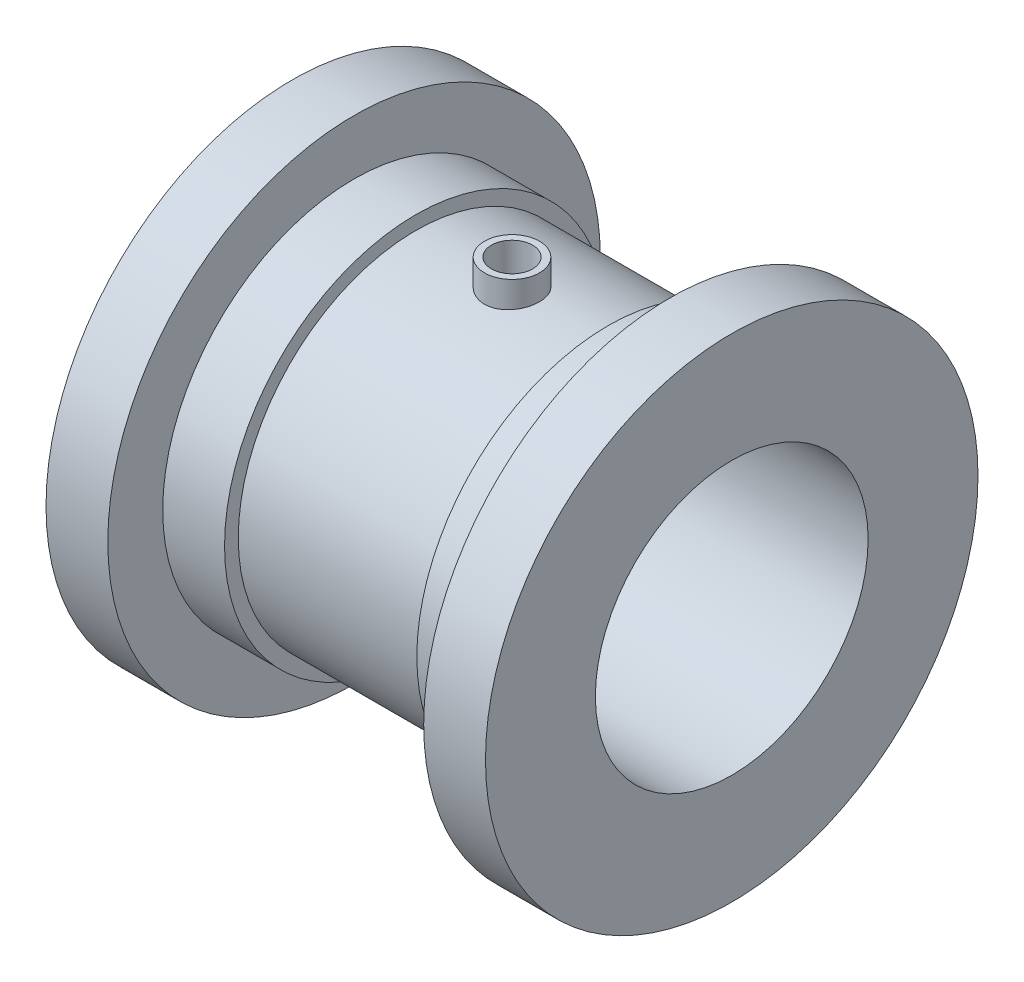
SolidWorks part; units mm, degrees
ref_plane "Front Plane" through (0, 0, 0) normal (0, 0, 1) x (1, 0, 0)
ref_plane "Top Plane" through (0, 0, 0) normal (0, 1, 0) x (1, 0, 0)
ref_plane "Right Plane" through (0, 0, 0) normal (1, 0, 0) x (0, 0, -1)
sketch "Sketch1" plane through (0, 0, 0) normal (0, 0, 1) x (1, 0, 0)
  line L0 (0, 32.4987) -> (0, -31.5139) construction
  line L1 (-45.6358, 0.4924) -> (36.1034, 0.4924) construction
  line L2 (-32, 20.3527) -> (32, 20.3527)
  line L3 (32, 20.3527) -> (32, 36.3527)
  line L4 (32, 36.3527) -> (23, 36.3527)
  line L5 (23, 36.3527) -> (23, 28.3527)
  line L6 (23, 28.3527) -> (14, 28.3527)
  line L7 (14, 28.3527) -> (14, 26.3527)
  line L8 (14, 26.3527) -> (-14, 26.3527)
  line L9 (-32, 20.3527) -> (-32, 36.3527)
  line L10 (-32, 36.3527) -> (-23, 36.3527)
  line L11 (-23, 36.3527) -> (-23, 28.3527)
  line L12 (-23, 28.3527) -> (-14, 28.3527)
  line L13 (-14, 28.3527) -> (-14, 26.3527)
  point P9 (0, 29.0519)
  point P15 (0, 20.3527)
  point P20 (0, 26.3527)
  dimension "D1" = 32
  dimension "D2" = 20.3527
  dimension "D3" = 16
  dimension "D4" = 9
  dimension "D5" = 46
  dimension "D6" = 28
  dimension "D7" = 2
  dimension "D8" = 8
revolve "Revolve1" add sketch "Sketch1" angle 360 about L1
sketch "Sketch2" plane through (0, 0, 0) normal (0, 1, 0) x (1, 0, 0)
  circle A0 centre (0, 0) radius 3
  dimension "D1" = 6
extrude "Cut-Extrude1" cut sketch "Sketch2" against normal through all both and the other way through all
ref_plane "Plane1" through (0, 30, 0) normal (0, 1, 0) x (1, 0, 0)
sketch "Sketch3" plane through (0, 30, 0) normal (0, 1, 0) x (1, 0, 0)
  circle A0 centre (0, 0) radius 3
  circle A1 centre (0, 0) radius 4
  dimension "D1" = 6
  dimension "D2" = 8
extrude "Boss-Extrude1" add sketch "Sketch3" against normal up to next
